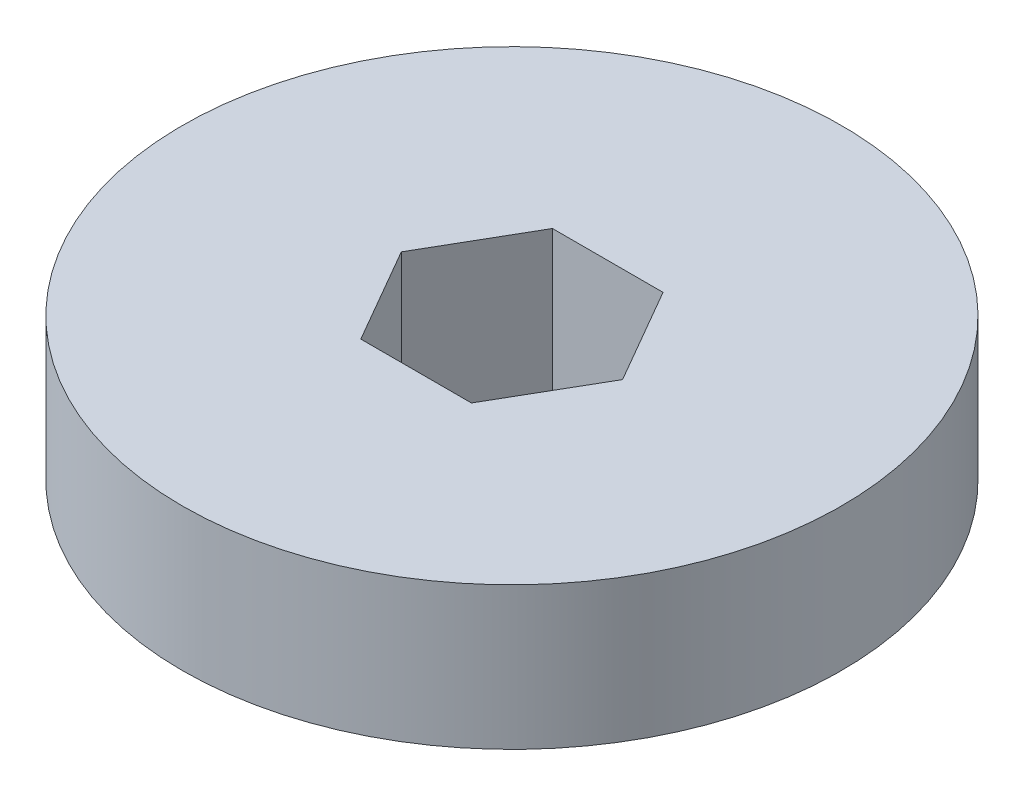
SolidWorks part; units mm, degrees
material "1060 Alloy"
ref_plane "Front Plane" through (0, 0, 0) normal (0, 0, 1) x (1, 0, 0)
ref_plane "Top Plane" through (0, 0, 0) normal (0, 1, 0) x (1, 0, 0)
ref_plane "Right Plane" through (0, 0, 0) normal (1, 0, 0) x (0, 0, -1)
sketch "Sketch1" plane through (0, 0, 0) normal (0, 1, 0) x (1, 0, 0)
  line L1 (-3.6662, 6.35) -> (-7.3323, 0)
  line L2 (-7.3323, 0) -> (-3.6662, -6.35)
  line L3 (-3.6662, -6.35) -> (3.6662, -6.35)
  line L4 (3.6662, -6.35) -> (7.3323, 0)
  line L5 (7.3323, 0) -> (3.6662, 6.35)
  line L6 (3.6662, 6.35) -> (-3.6662, 6.35)
  circle A0 centre (0, 0) radius 21.844
  circle A1 centre (0, 0) radius 6.35 construction
  dimension "D1" = 43.688
  dimension "D2" = 12.7
extrude "Boss-Extrude1" add sketch "Sketch1" along normal blind 9.4488
